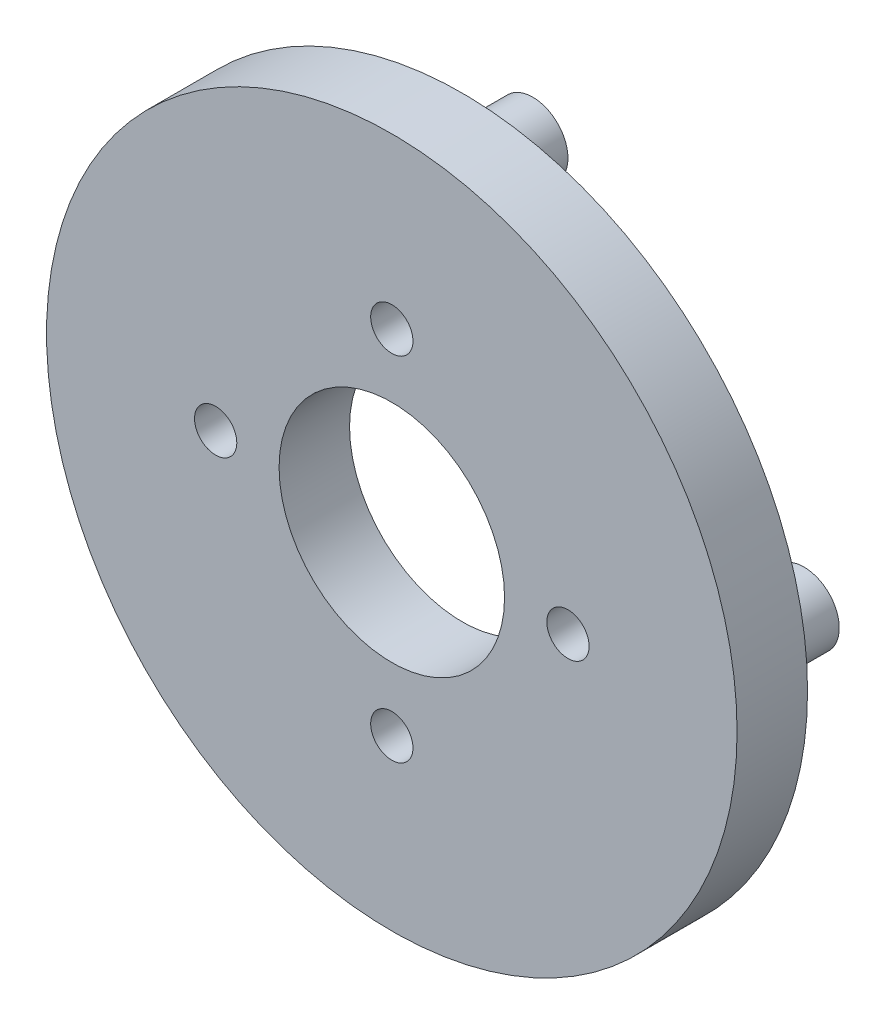
SolidWorks part; units mm, degrees
ref_plane "前视基准面" through (0, 0, 0) normal (0, 0, 1) x (1, 0, 0)
ref_plane "上视基准面" through (0, 0, 0) normal (0, 1, 0) x (1, 0, 0)
ref_plane "右视基准面" through (0, 0, 0) normal (1, 0, 0) x (0, 0, -1)
sketch "草图1" plane through (0, 0, 0) normal (0, 0, 1) x (1, 0, 0)
  circle A0 centre (0, 0) radius 24.5
  circle A2 centre (0, 12.5) radius 1.5
  circle A3 centre (12.5, 0) radius 1.5
  circle A4 centre (0, -12.5) radius 1.5
  circle A5 centre (-12.5, 0) radius 1.5
  point P15 (0, 0)
  dimension "D1" = 49
  dimension "D2" = 4
extrude "凸台-拉伸1" add sketch "草图1" along normal blind 5
sketch "草图2" plane through (0, 0, 0) normal (0, 0, 1) x (1, 0, 0)
  circle A1 centre (0, 19.25) radius 2.5
  circle A2 centre (19.25, 0) radius 2.5
  circle A3 centre (0, -19.25) radius 2.5
  circle A4 centre (-19.25, 0) radius 2.5
  point P14 (0, 0)
  dimension "D1" = 4
extrude "凸台-拉伸2" add sketch "草图2" against normal blind 5
sketch "草图4" plane through (0, 0, 0) normal (0, 0, 1) x (1, 0, 0)
  circle A0 centre (0, 19.25) radius 1.25
  circle A1 centre (19.25, 0) radius 1.25
  circle A2 centre (0, -19.25) radius 1.25
  circle A3 centre (-19.25, 0) radius 1.25
  point P12 (0, 0)
  dimension "D1" = 4
extrude "切除-拉伸1" cut sketch "草图4" against normal blind 5
sketch "草图5" plane through (0, 0, 0) normal (0, 0, 1) x (1, 0, 0)
  circle A0 centre (0, 0) radius 8
extrude "切除-拉伸2" cut sketch "草图5" along normal blind 5
sketch "草图6" plane through (0, 0, 0) normal (0, 0, 1) x (1, 0, 0)
  circle A0 centre (0, 12.5) radius 2.5
  circle A1 centre (12.5, 0) radius 2.5
  circle A2 centre (0, -12.5) radius 2.5
  circle A3 centre (-12.5, 0) radius 2.5
  circle A4 centre (0, 0) radius 12.5 construction
  point P11 (0, 0)
  dimension "D1" = 4
extrude "切除-拉伸3" cut sketch "草图6" along normal blind 2
